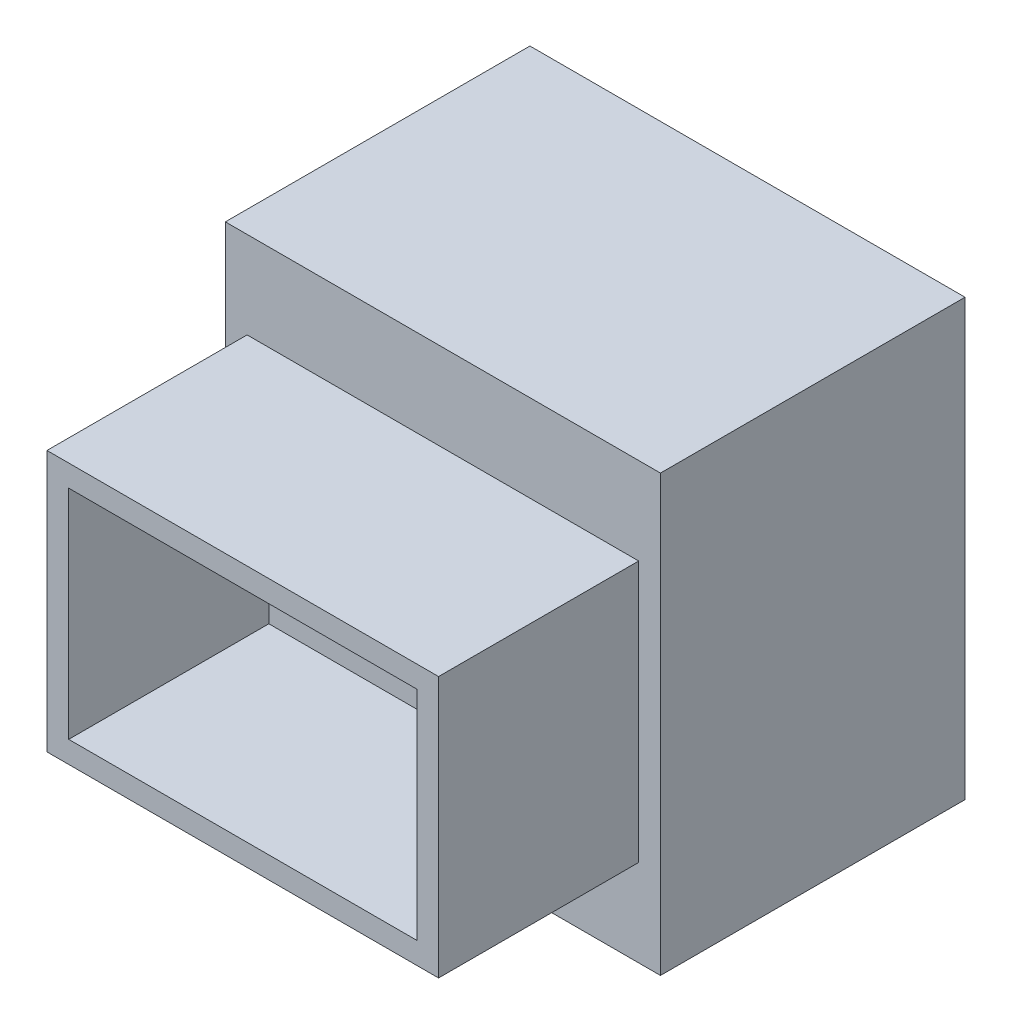
SolidWorks part; units mm, degrees
ref_plane "Front Plane" through (0, 0, 0) normal (0, 0, 1) x (1, 0, 0)
ref_plane "Top Plane" through (0, 0, 0) normal (0, 1, 0) x (1, 0, 0)
ref_plane "Right Plane" through (0, 0, 0) normal (1, 0, 0) x (0, 0, -1)
sketch "Sketch1" plane through (0, 0, 0) normal (0, 0, 1) x (1, 0, 0)
  line L1 (50, 50) -> (-50, 50)
  line L2 (50, 50) -> (50, -50)
  line L3 (50, -50) -> (-50, -50)
  line L4 (-50, 50) -> (-50, -50)
  line L5 (50, 50) -> (-50, -50) construction
  line L6 (50, -50) -> (-50, 50) construction
  point P0 (0, 0)
  dimension "D1" = 100
  dimension "D2" = 100
extrude "Boss-Extrude1" add sketch "Sketch1" along normal blind 70
sketch "Sketch2" plane through (0, 0, 70) normal (0, 0, 1) x (1, 0, 0)
  line L1 (40, 25) -> (-40, 25)
  line L2 (40, 25) -> (40, -25)
  line L3 (40, -25) -> (-40, -25)
  line L4 (-40, 25) -> (-40, -25)
  line L5 (40, 25) -> (-40, -25) construction
  line L6 (40, -25) -> (-40, 25) construction
  line L7 (45, 30) -> (-45, 30)
  line L8 (45, 30) -> (45, -30)
  line L9 (45, -30) -> (-45, -30)
  line L10 (-45, 30) -> (-45, -30)
  line L11 (45, 30) -> (-45, -30) construction
  line L12 (45, -30) -> (-45, 30) construction
  point P0 (0, 0)
  point P6 (0, 0)
  dimension "D1" = 80
  dimension "D2" = 50
  dimension "D3" = 5
  dimension "D4" = 5
extrude "Boss-Extrude2" add sketch "Sketch2" along normal blind 46
